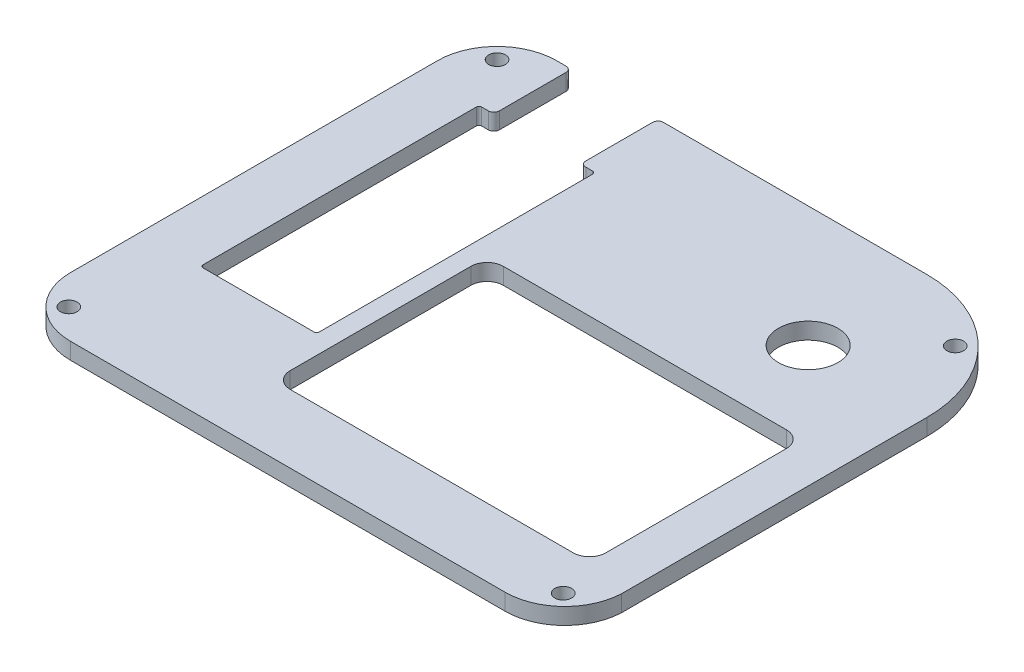
SolidWorks part; units mm, degrees
material "PMMA"
ref_plane "Front Plane" through (0, 0, 0) normal (0, 0, 1) x (1, 0, 0)
ref_plane "Top Plane" through (0, 0, 0) normal (0, 1, 0) x (1, 0, 0)
ref_plane "Right Plane" through (0, 0, 0) normal (1, 0, 0) x (0, 0, -1)
sketch "Sketch2" plane through (0, 0, 0) normal (0, 1, 0) x (1, 0, 0)
  line L0 (28, -66.24) -> (28, -32.84)
  line L1 (3, 0) -> (71.45, 0) construction
  line L2 (0, -3) -> (0, -70.84) construction
  line L3 (3, -73.84) -> (83.3401, -73.84) construction
  line L9 (3, -6.34) -> (3.5, -6.34) construction
  line L10 (3, -6.84) -> (3, -57.34)
  line L11 (3, -57.84) -> (3.5, -57.84) construction
  line L12 (24.5, -6.84) -> (24.5, -57.34)
  line L22 (86.33, -14.88) -> (86.33, -71.0854) construction
  line L23 (31, -29.84) -> (83.33, -29.84)
  line L24 (31, -69.24) -> (83.33, -69.24)
  line L25 (3, 8) -> (4.75, 8)
  line L26 (94.33, -14.88) -> (94.33, -71.3101)
  line L27 (3, -81.84) -> (83.3401, -81.84)
  line L28 (-8, -3) -> (-8, -70.84)
  line L29 (86.33, -32.84) -> (86.33, -66.24)
  line L30 (0.8787, -0.8787) -> (-4.7782, 4.7782) construction
  line L31 (81.9717, -4.3583) -> (87.6286, 1.2986) construction
  line L32 (90.9502, -78.7827) -> (85.3728, -73.0464) construction
  line L33 (-4.7782, -78.6182) -> (0.8787, -72.9613) construction
  line L34 (24, -6.34) -> (22.75, -6.34)
  line L35 (3.5, -57.84) -> (24, -57.84)
  line L36 (13.75, -6.34) -> (13.75, 8) construction
  line L37 (21.75, -5.34) -> (21.75, 7)
  line L38 (5.75, -5.34) -> (5.75, 7)
  line L39 (4.75, -6.34) -> (3.5, -6.34)
  line L40 (22.75, 8) -> (71.45, 8)
  line L41 (3, 8) -> (71.45, 8) construction
  line L42 (5.75, -6.34) -> (5.75, 8) construction
  line L43 (21.75, -6.34) -> (21.75, 8) construction
  arc A0 (86.33, -14.88) -> (71.45, 0) centre (71.45, -14.88) ccw construction
  circle A6 centre (82.13, -71.01) radius 1.1 construction
  circle A7 centre (82.13, -26.2) radius 1.1 construction
  circle A8 centre (71.83, -14.33) radius 5.5
  arc A9 (86.33, -71.0854) -> (83.3401, -73.84) centre (83.3401, -70.84) cw construction
  arc A10 (0, -70.84) -> (3, -73.84) centre (3, -70.84) ccw construction
  arc A11 (3, 0) -> (0, -3) centre (3, -3) ccw construction
  arc A13 (28, -66.24) -> (31, -69.24) centre (31, -66.24) ccw
  arc A14 (28, -32.84) -> (31, -29.84) centre (31, -32.84) cw
  arc A17 (3, -57.34) -> (3.5, -57.84) centre (3.5, -57.34) ccw
  arc A19 (24.5, -57.34) -> (24, -57.84) centre (24, -57.34) cw
  arc A20 (24.5, -6.84) -> (24, -6.34) centre (24, -6.84) ccw
  arc A23 (3, -6.84) -> (3.5, -6.34) centre (3.5, -6.84) cw
  arc A24 (94.33, -14.88) -> (71.45, 8) centre (71.45, -14.88) ccw
  arc A25 (94.33, -71.3101) -> (83.3401, -81.84) centre (83.3401, -70.84) cw
  arc A26 (-8, -70.84) -> (3, -81.84) centre (3, -70.84) ccw
  arc A27 (3, 8) -> (-8, -3) centre (3, -3) ccw
  arc A28 (86.33, -32.84) -> (83.33, -29.84) centre (83.33, -32.84) ccw
  arc A29 (86.33, -66.24) -> (83.33, -69.24) centre (83.33, -66.24) cw
  circle A30 centre (-2.6569, 2.6569) radius 1.55
  circle A31 centre (85.5073, -0.8227) radius 1.55
  circle A32 centre (88.8589, -76.6318) radius 1.55
  circle A33 centre (-2.6569, -76.4969) radius 1.55
  arc A34 (5.75, 7) -> (4.75, 8) centre (4.75, 7) ccw
  arc A35 (22.75, 8) -> (21.75, 7) centre (22.75, 7) ccw
  arc A36 (21.75, -5.34) -> (22.75, -6.34) centre (22.75, -5.34) ccw
  arc A37 (5.75, -5.34) -> (4.75, -6.34) centre (4.75, -5.34) cw
  point P37 (86.33, -73.84)
  point P40 (0, -73.84)
  point P43 (0, 0)
  point P55 (6.5, -57.84)
  point P61 (21, -57.84)
  point P70 (21, -6.34)
  point P73 (6.5, -6.34)
  point P86 (86.33, -29.84)
  point P89 (86.33, -69.24)
  dimension "D1" = 14.88
  dimension "D6" = 8
  dimension "D28" = 11
  dimension "D29" = 3
  dimension "D30" = 3
  dimension "D31" = 3
  dimension "D32" = 3
  dimension "D33" = 3
  dimension "D34" = 3
  dimension "D35" = 3
  dimension "D37" = 0.5
  dimension "D39" = 0.5
  dimension "D40" = 0.5
  dimension "D43" = 0.5
  dimension "D20" = 3
  dimension "D44" = 3.1
  dimension "D46" = 3.1
  dimension "D48" = 3.1
  dimension "D50" = 3.1
  dimension "D8" = 1
  dimension "D9" = 1
  dimension "D10" = 1
  dimension "D11" = 1
  dimension "D2" = 73.84
  dimension "D3" = 86.33
  dimension "D7" = 8
  dimension "D13" = 8
  dimension "D14" = 4.6
  dimension "D15" = 2.83
  dimension "D17" = 26.2
  dimension "D18" = 28
  dimension "D19" = 44
  dimension "D21" = 16
  dimension "D23" = 3
  dimension "D24" = 51.5
  dimension "D27" = 14.33
  dimension "D45" = 3
  dimension "D47" = 3
  dimension "D49" = 3
extrude "Boss-Extrude1" add sketch "Sketch2" along normal blind 3.048
